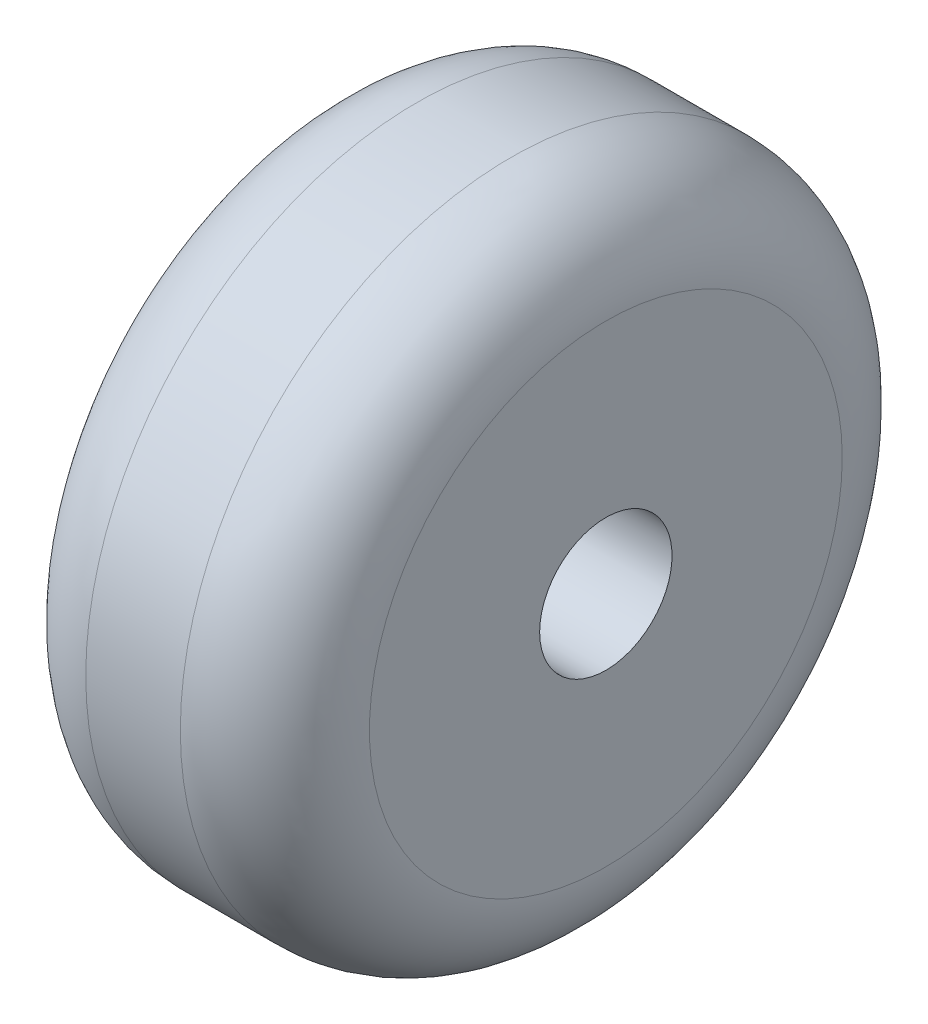
SolidWorks part; units mm, degrees
ref_plane "Front Plane" through (0, 0, 0) normal (0, 0, 1) x (1, 0, 0)
ref_plane "Top Plane" through (0, 0, 0) normal (0, 1, 0) x (1, 0, 0)
ref_plane "Right Plane" through (0, 0, 0) normal (1, 0, 0) x (0, 0, -1)
sketch "Sketch1" plane through (0, 0, 0) normal (1, 0, 0) x (0, 0, -1)
  circle A0 centre (0, 0) radius 88.9
extrude "Boss-Extrude1" add sketch "Sketch1" along normal blind 76.2
fillet "Fillet1" radius 25.4 1 edges at (76.2, 0, -88.9)
fillet "Fillet2" radius 25.4 1 edges at (0, 0, -88.9)
ref_point "Point1"
sketch "Sketch2" plane through (0, 0, 0) normal (-1, 0, 0) x (0, 0, 1)
  circle A0 centre (0, 0) radius 17.78
  dimension "D1" = 35.56
extrude "Cut-Extrude1" cut sketch "Sketch2" against normal through all both and the other way through all
